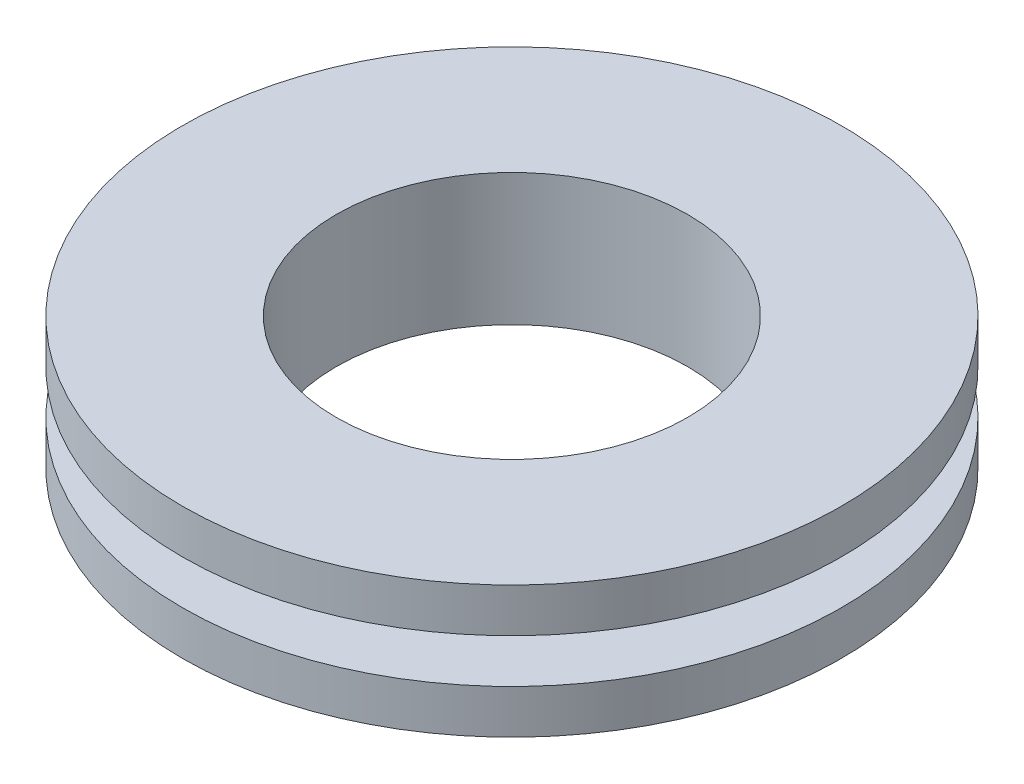
SolidWorks part; units mm, degrees
ref_plane "Plan de face" through (0, 0, 0) normal (0, 0, 1) x (1, 0, 0)
ref_plane "Plan de dessus" through (0, 0, 0) normal (0, 1, 0) x (1, 0, 0)
ref_plane "Plan de droite" through (0, 0, 0) normal (1, 0, 0) x (0, 0, -1)
sketch "Sketch1" plane through (0, 0, 0) normal (0, 0, 1) x (1, 0, 0)
  line L0 (0, 5.8706) -> (0, -4.3819) construction
  line L8 (4, 1.5) -> (4, -1.5)
  line L9 (4, 1.5) -> (7.5, 1.5)
  line L10 (7.5, 1.5) -> (7.5, 0.5)
  line L11 (7.5, 0.5) -> (6, 0.5)
  line L12 (6, 0.5) -> (6, -0.5)
  line L13 (6, -0.5) -> (7.5, -0.5)
  line L14 (7.5, -0.5) -> (7.5, -1.5)
  line L15 (7.5, -1.5) -> (4, -1.5)
  point P4 (4, 0)
  dimension "D2" = 2
  dimension "D3" = 1.5
  dimension "D5" = 1
  dimension "D1" = 4
  dimension "D4" = 3
revolve "Revolve1" add sketch "Sketch1" angle 360 about L0
